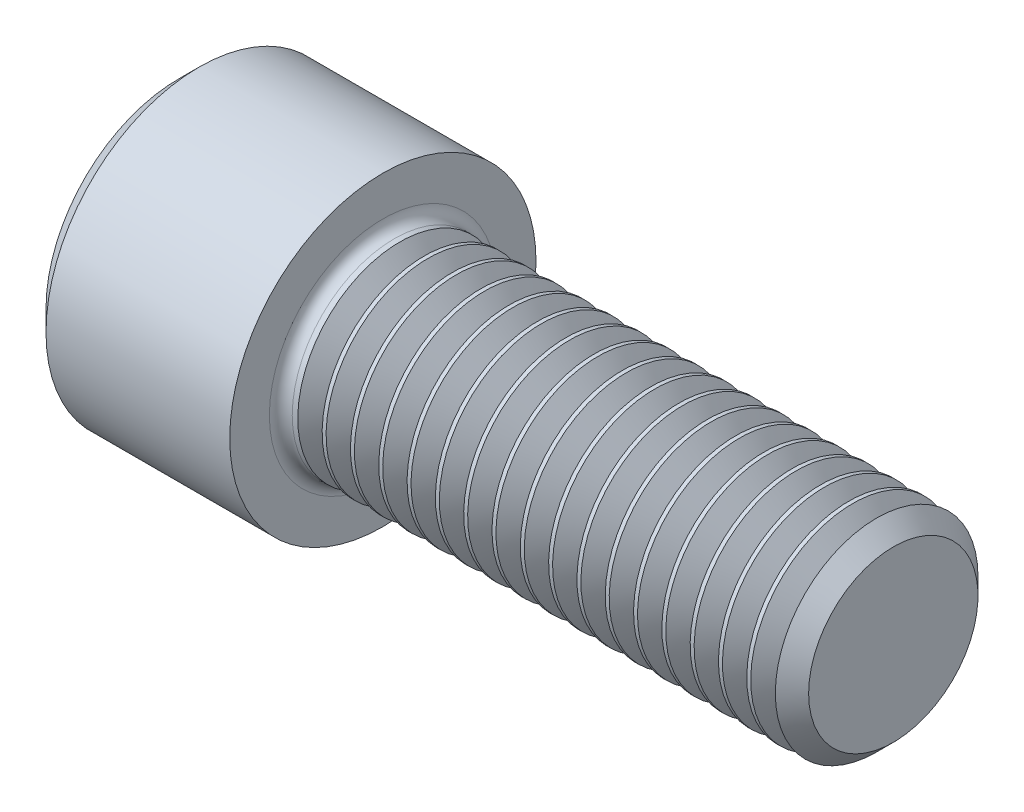
SolidWorks part; units mm, degrees
revolve "Base-Revolve" add sketch "BodySke"
sketch "BodySke" plane through (0, 0, 0) normal (0, 0, 1) x (1, 0, 0)
  line L0 (0, 0) -> (0, 4.1275)
  line L1 (0.635, 4.7625) -> (6.35, 4.7625)
  line L2 (6.35, 4.7625) -> (6.35, 3.175)
  line L3 (6.35, 3.175) -> (21.684, 3.175)
  line L4 (22.225, 2.634) -> (22.225, 0)
  line L5 (22.225, 0) -> (0, 0)
  line L6 (-31.75, 0) -> (127, 0) construction
  line L7 (0, 4.1275) -> (0.635, 4.7625)
  line L8 (22.225, 2.634) -> (21.684, 3.175)
  line L9 (0, -4.1275) -> (0.635, -4.7625) construction
  line L10 (22.225, -2.634) -> (21.684, -3.175) construction
  line L11 (7.2568, 9.525) -> (7.2568, 3.175) construction
  line L12 (6.35, 9.525) -> (6.35, 3.175) construction
  line L13 (-15.875, 9.525) -> (-15.875, 3.175) construction
  dimension "Diameter" = 6.35
  dimension "Head_ht" = 6.35
  dimension "Length" = 15.875
  dimension "Body_ch_ang" = 45
  dimension "Head_dia" = 9.525
  dimension "Head_ch_ang" = 45
  dimension "Head_side_ht" = 5.715
  dimension "Minor_dia" = 5.268
  dimension "Advance" = 0.9068
  dimension "Thread_nom" = 15.875
  dimension "Thread_length" = 38.1
cosmetic thread "ThreadCosmetic" [suppressed]
fillet "Fillet1" radius 0.3556 1 edges at (6.35, 0, 3.175)
ref_plane "Plane1" through (0, 0, 0) normal (0, 0, 1) x (1, 0, 0)
ref_plane "Plane2" through (0, 0, 0) normal (0, 1, 0) x (1, 0, 0)
ref_plane "Plane3" through (0, 0, 0) normal (1, 0, 0) x (0, 0, -1)
sketch "Sketch2" plane through (0, 0, 0) normal (0, 0, 1) x (1, 0, 0)
  line L0 (0, 2.3813) -> (3.048, 2.3813)
  line L1 (3.048, 2.3813) -> (4.4228, 0)
  line L2 (-31.75, 0) -> (127, 0) construction
  line L3 (4.4228, 0) -> (0, 0)
  line L4 (0, 0) -> (0, 2.3813)
  line L5 (0, 4.1275) -> (0, -4.1275) construction
  line L6 (0, 0) -> (47.625, 0) construction
  line L7 (6.35, -4.7625) -> (6.35, 4.7625) construction
  dimension "D1" = 2.3813
  dimension "D2" = 60
revolve "Hex-PreBroach" cut sketch "Sketch2" angle 360 about L6
sketch "Sketch3" plane through (0, 0, 0) normal (-1, 0, 0) x (0, 0.5, 0.866)
  line L0 (1.3748, 2.3813) -> (-1.3748, 2.3813)
  line L1 (-1.3748, 2.3813) -> (-2.7496, 0)
  line L2 (1.3748, 2.3813) -> (2.7496, 0)
  line L3 (1.3748, -2.3812) -> (2.7496, 0)
  line L4 (1.3748, -2.3812) -> (-1.3748, -2.3812)
  line L5 (-1.3748, -2.3812) -> (-2.7496, 0)
  dimension "D1" = 2.3813
  dimension "D2" = 2.3813
  dimension "Hex_size" = 4.7625
extrude "Hex" cut sketch "Sketch3" against normal blind 3.048
sketch "Sketch4" plane through (0, 0, 0) normal (-1, 0, 0) x (0, 0, 1)
  line L0 (0, 0) -> (2.8067, 0)
  line L1 (0, 0) -> (6.1484, 3.5498) construction
  line L2 (0, 0) -> (1.4033, 2.4307)
  line L3 (2.3336, 0.614) -> (2.6851, 0.817)
  line L4 (1.6986, 1.7139) -> (2.0501, 1.9169)
  arc A0 (2.3336, 0.614) -> (1.6986, 1.7139) centre (0, 0) ccw
  arc A1 (2.8067, 0) -> (2.6851, 0.817) centre (0, 0) ccw
  arc A2 (1.4033, 2.4307) -> (2.0501, 1.9169) centre (0, 0) cw
  dimension "D1" = 30
  dimension "D2" = 60
  dimension "Spline_p_dim" = 1.27
  dimension "D3" = 0.635
extrude "Spline" [suppressed] cut sketch "Sketch4" against normal blind 3.048
pattern_circular "CirPattern1" [suppressed] count 6 every 60
sketch "Sketch5" plane through (0, 0, 0) normal (0, 0, 1) x (1, 0, 0)
  line L0 (-31.75, 0) -> (127, 0) construction
  line L2 (0, 4.1275) -> (0, -4.1275) construction
  circle A0 centre (2.159, 0) radius 0.5905
  dimension "Drilled_hole_dia" = 1.1811
  dimension "Drilled_hole_loc" = 2.159
extrude "Hole" [suppressed] cut sketch "Sketch5" against normal through all and the other way through all
pattern_circular "Drilled-4" [suppressed] count 2 every 60
pattern_circular "Drilled-6" [suppressed] count 3 every 60
sketch "ThdSchSke" plane through (0, 0, 0) normal (0, 0, 1) x (1, 0, 0)
  line L0 (7.2568, -2.634) -> (6.878, -3.175)
  line L1 (7.2568, -2.634) -> (7.6356, -3.175)
  line L2 (7.6356, -3.175) -> (7.6356, -3.9688)
  line L3 (-3.175, 0) -> (5.1513, 0) construction
  line L5 (7.6356, -3.9688) -> (6.878, -3.9688)
  line L6 (6.878, -3.9688) -> (6.878, -3.175)
  line L7 (0, 4.1275) -> (0, -4.1275) construction
  dimension "Thread_minor" = 5.268
  dimension "Diameter" = 6.35
  dimension "Start" = 7.2568
revolve "ThreadSchematic" cut sketch "ThdSchSke" angle 360 about L3
pattern_linear "ThdSchPat" count 17 spacing 0.8805 along (1, 0, 0) of "ThreadSchematic"
equation "\"D2@Sketch3\" = \"Hex_size@Sketch3\" / 2"
equation "\"D1@Sketch3\" = \"Hex_size@Sketch3\" / 2"
equation "\"D1@Sketch2\" = \"Hex_size@Sketch3\" / 2"
equation "\"D3@Sketch4\" = \"Spline_p_dim@Sketch4\" / 2"
equation "\"Thread_minor@ThreadCosmetic\"  =  \"Minor_dia@BodySke\""
equation "\"D2@CirPattern1\" = 360 / \"Num_teeth@CirPattern1\""
equation "\"Wall_thickness@Sketch2\" = \"Head_ht@BodySke\" - \"Key_eng@Hex\""
equation "\"Thread_length@ThreadCosmetic\" = ((sgn( (\"Length@BodySke\" - \"Advance@BodySke\" ) - \"Thread_nom@BodySke\" )-1)*( (\"Length@BodySke\" - \"Advance@BodySke\" ) - \"Thread_nom@BodySke\" ))/-2+ \"Thread_nom@BodySke\""
equation "\"Thread_minor@ThdSchSke\" = \"Minor_dia@BodySke\""
equation "\"Diameter@ThdSchSke\" = \"Diameter@BodySke\""
equation "\"Overcut@ThdSchSke\" = \"Diameter@BodySke\" * 1.25"
equation "\"Start@ThdSchSke\" = \"Head_ht@BodySke\" + \"Length@BodySke\" - \"Thread_length@ThreadCosmetic\"  '---Non-countersunk---"
equation "\"Num_threads@ThdSchPat\" = int( \"Thread_length@ThreadCosmetic\" / \"Advance@BodySke\" + 0.999 )  + 1"
equation "\"Advance@ThdSchPat\" = \"Thread_length@ThreadCosmetic\" /  (\"Num_threads@ThdSchPat\" - 1) 'relax it"
equation "\"Num_threads@ThdSchPat\" = \"Num_threads@ThdSchPat\" - sgn( \"Num_threads@ThdSchPat\" - 1) '---chamfered tips only---"
